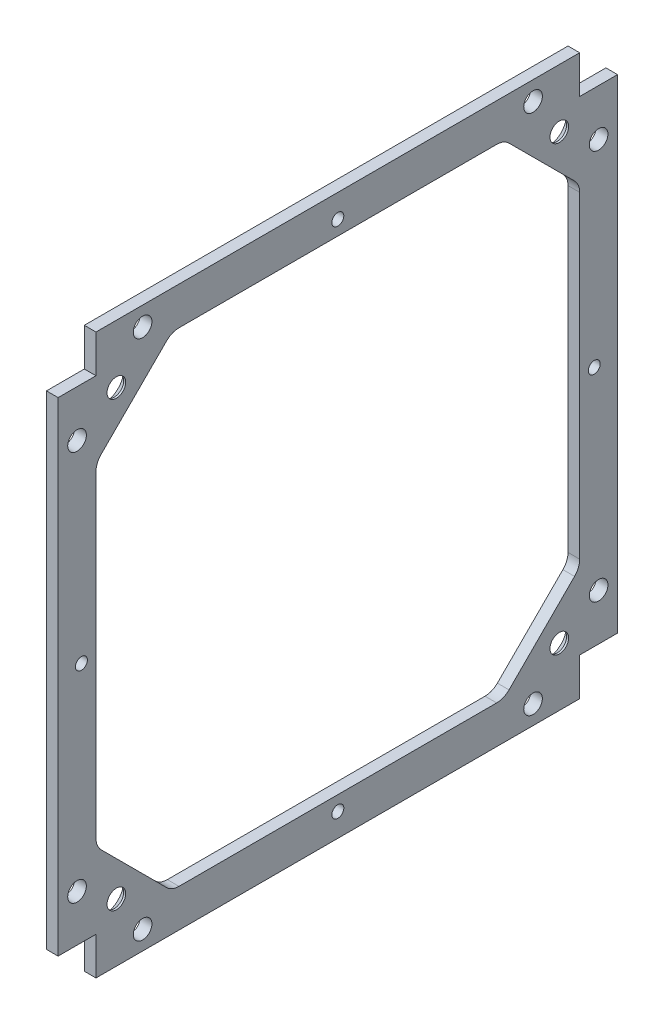
SolidWorks part; units mm, degrees
ref_plane "Front Plane" through (0, 0, 0) normal (0, 0, 1) x (1, 0, 0)
ref_plane "Top Plane" through (0, 0, 0) normal (0, 1, 0) x (1, 0, 0)
ref_plane "Right Plane" through (0, 0, 0) normal (1, 0, 0) x (0, 0, -1)
sketch "Sketch2" plane through (-51.4936, 0, 0) normal (-1, 0, 0) x (0, 0, 1)
  line L0 (0.9347, 3.4519) -> (7.4347, 3.4519)
  line L1 (7.4347, 3.4519) -> (7.4347, 86.4519)
  line L2 (0.9347, 92.9519) -> (-82.0653, 92.9519)
  line L3 (-88.5653, 86.4519) -> (-88.5653, 3.4519)
  line L4 (-82.0653, -3.0481) -> (0.9347, -3.0481)
  line L5 (0.9347, -3.0481) -> (0.9347, 3.4519)
  line L6 (-82.0653, -3.0481) -> (-82.0653, 3.4519)
  line L7 (-82.0653, 3.4519) -> (-88.5653, 3.4519)
  line L9 (-82.0653, 73.4519) -> (-82.0653, 16.4519)
  line L11 (-88.5653, 86.4519) -> (-82.0653, 86.4519)
  line L12 (-82.0653, 92.9519) -> (-82.0653, 86.4519)
  line L13 (-69.0653, 3.4519) -> (-12.0653, 3.4519)
  line L14 (-82.0653, 73.4519) -> (-69.0653, 86.4519)
  line L15 (7.4347, 86.4519) -> (0.9347, 86.4519)
  line L16 (0.9347, 92.9519) -> (0.9347, 86.4519)
  line L17 (0.9347, 16.4519) -> (0.9347, 73.4519)
  line L18 (-12.0653, 86.4519) -> (0.9347, 73.4519)
  line L19 (-12.0653, 86.4519) -> (-69.0653, 86.4519)
  line L28 (-12.0653, 3.4519) -> (0.9347, 16.4519)
  line L29 (-82.0653, 16.4519) -> (-69.0653, 3.4519)
  dimension "D21" = 13
  dimension "D1" = 6.5
  dimension "D2" = 6.5
  dimension "D3" = 6.5
  dimension "D4" = 6.5
  dimension "D5" = 6.5
  dimension "D6" = 6.5
  dimension "D7" = 13
  dimension "D8" = 6.5
  dimension "D9" = 6.5
  dimension "D10" = 13
  dimension "D11" = 6.5
  dimension "D12" = 6.5
  dimension "D14" = 13
  dimension "D15" = 13
  dimension "D16" = 13
  dimension "D17" = 13
  dimension "D18" = 13
  dimension "D19" = 83
  dimension "D20" = 83
extrude "Boss-Extrude2" add sketch "Sketch2" along normal blind 2
hole_wizard "Ø3.2 (3.2) Diameter Hole3" positions "Sketch19" profile "Sketch18" hole size "Ø3.2" standard "Ansi Metric" end condition up to next
sketch "Sketch19" plane through (-53.4936, 0, 0) normal (-1, 0, 0) x (0, 0, 1)
  line L0 (-82.0653, 3.4519) -> (-82.0653, -3.0481) construction
  line L1 (-82.0653, -3.0481) -> (0.9347, -3.0481) construction
  line L2 (0.9347, -3.0481) -> (0.9347, 3.4519) construction
  line L3 (-88.5653, 86.4519) -> (-88.5653, 3.4519) construction
  line L4 (-88.5653, 3.4519) -> (-82.0653, 3.4519) construction
  line L5 (7.4347, 3.4519) -> (7.4347, 86.4519) construction
  line L6 (0.9347, 3.4519) -> (7.4347, 3.4519) construction
  line L7 (7.4347, 86.4519) -> (0.9347, 86.4519) construction
  line L8 (0.9347, 86.4519) -> (0.9347, 92.9519) construction
  line L9 (0.9347, 92.9519) -> (-82.0653, 92.9519) construction
  line L11 (-82.0653, 92.9519) -> (-82.0653, 86.4519) construction
  line L12 (-82.0653, 86.4519) -> (-88.5653, 86.4519) construction
  point P0 (-74.0653, 0.2019)
  point P7 (-85.3153, 11.4519)
  point P9 (-85.3153, 78.4519)
  point P11 (-74.0653, 89.7019)
  point P13 (-7.0653, 89.7019)
  point P15 (4.1847, 78.4519)
  point P17 (4.1847, 11.4519)
  point P19 (-7.0653, 0.2019)
  dimension "D1" = 8
  dimension "D2" = 3.25
  dimension "D3" = 8
  dimension "D4" = 3.25
  dimension "D5" = 8
  dimension "D6" = 3.25
  dimension "D7" = 8
  dimension "D8" = 8
  dimension "D9" = 8
  dimension "D10" = 3.25
  dimension "D11" = 8
  dimension "D12" = 8
sketch "Sketch18" plane through (-53.4936, 0.2019, -74.0653) normal (0, 1, 0) x (0, 0, 1)
  line L0 (0, 0) -> (0, 2)
  line L1 (0, 2) -> (1.6, 2)
  line L2 (1.6, 2) -> (1.6, 0)
  line L5 (1.6, 0) -> (0, 0)
  line L11 (0, -6.35) -> (0, 107.95) construction
  dimension "Thru Hole Dia." = 3.2
  dimension "Thru Hole Depth" = 2
sketch "Sketch20" plane through (-53.4936, 0, 0) normal (-1, 0, 0) x (0, 0, 1)
  line L0 (-88.5653, 3.4519) -> (-82.0653, 3.4519) construction
  line L1 (-88.5653, 86.4519) -> (-88.5653, 3.4519) construction
  line L2 (-82.0653, 86.4519) -> (-88.5653, 86.4519) construction
  line L3 (-82.0653, 92.9519) -> (-82.0653, 86.4519) construction
  line L4 (0.9347, 92.9519) -> (-82.0653, 92.9519) construction
  line L5 (0.9347, 86.4519) -> (0.9347, 92.9519) construction
  line L6 (7.4347, 86.4519) -> (0.9347, 86.4519) construction
  line L7 (7.4347, 3.4519) -> (7.4347, 86.4519) construction
  point P0 (-85.5653, 6.9519)
  point P1 (-85.5653, 82.9519)
  point P2 (-78.5653, 89.9519)
  point P3 (-2.5653, 89.9519)
  point P4 (4.4347, 82.9519)
  dimension "D1" = 3.5
  dimension "D2" = 3
  dimension "D3" = 3
  dimension "D4" = 3.5
  dimension "D5" = 3.5
  dimension "D6" = 3
  dimension "D7" = 3
  dimension "D8" = 3.5
  dimension "D9" = 3.5
  dimension "D10" = 3
hole_wizard "CSK for M3 Flat Countersunk Head Screw5" positions "3DSketch2" profile "Sketch24" countersink size "M3" standard "JIS" end condition up to next
sketch3d "3DSketch2"
  line L0 (-53.4936, 3.4519, -82.0653) -> (-53.4936, -3.0481, -82.0653) construction
  line L1 (-53.4936, 3.4519, -88.5653) -> (-53.4936, 3.4519, -82.0653) construction
  line L2 (-53.4936, 92.9519, -82.0653) -> (-53.4936, 86.4519, -82.0653) construction
  line L3 (-53.4936, 86.4519, -82.0653) -> (-53.4936, 86.4519, -88.5653) construction
  line L4 (-53.4936, 86.4519, 0.9347) -> (-53.4936, 92.9519, 0.9347) construction
  line L5 (-53.4936, 86.4519, 7.4347) -> (-53.4936, 86.4519, 0.9347) construction
  line L6 (-53.4936, -3.0481, 0.9347) -> (-53.4936, 3.4519, 0.9347) construction
  line L7 (-53.4936, 3.4519, 0.9347) -> (-53.4936, 3.4519, 7.4347) construction
  point P0 (-53.4936, 6.9519, -78.5653)
  point P2 (-53.4936, 82.9519, -78.5653)
  point P4 (-53.4936, 82.9519, -2.5653)
  point P19 (-53.4936, 6.9519, -2.5653)
  dimension "D1" = 3.5
  dimension "D2" = 3.5
  dimension "D3" = 3.5
  dimension "D4" = 3.5
  dimension "D5" = 3.5
  dimension "D6" = 3.5
  dimension "D7" = 3.5
  dimension "D8" = 3.5
sketch "Sketch24" plane through (-53.4936, 6.9519, -78.5653) normal (0, 1, 0) x (0, 0, 1)
  line L0 (0, 0) -> (0, 2)
  line L1 (0, 2) -> (1.6, 2)
  line L2 (1.6, 2) -> (1.6, 1.65)
  line L3 (1.6, 1.65) -> (3.25, 0)
  line L5 (3.25, 0) -> (0, 0)
  line L6 (-1.6, 1.65) -> (-3.25, 0) construction
  line L11 (0, -6.35) -> (0, 107.95) construction
  dimension "Thru Hole Dia." = 3.2
  dimension "Thru Hole Depth" = 2
  dimension "Near C'Sink Dia." = 6.5
  dimension "Near C'Sink Angle" = 90
hole_wizard "M2.5x0.45 Tapped Hole1" positions "3DSketch3" profile "Sketch25" tap size "M2.5x0.45" standard "Ansi Metric" end condition up to next
sketch3d "3DSketch3"
  line L0 (-53.4936, 92.9519, 0.9347) -> (-53.4936, 92.9519, -82.0653) construction
  line L1 (-53.4936, 86.4519, 0.9347) -> (-53.4936, 92.9519, 0.9347) construction
  line L2 (-53.4936, 86.4519, 7.4347) -> (-53.4936, 86.4519, 0.9347) construction
  line L3 (-53.4936, 3.4519, 7.4347) -> (-53.4936, 86.4519, 7.4347) construction
  line L4 (-53.4936, -3.0481, -82.0653) -> (-53.4936, -3.0481, 0.9347) construction
  line L5 (-53.4936, -3.0481, 0.9347) -> (-53.4936, 3.4519, 0.9347) construction
  line L6 (-53.4936, 86.4519, -88.5653) -> (-53.4936, 3.4519, -88.5653) construction
  line L7 (-53.4936, 3.4519, -88.5653) -> (-53.4936, 3.4519, -82.0653) construction
  point P0 (-53.4936, 88.9519, -40.5653)
  point P2 (-53.4936, 44.9519, -84.5653)
  point P4 (-53.4936, 0.9519, -40.5653)
  point P6 (-53.4936, 44.9519, 3.4347)
  dimension "D1" = 4
  dimension "D2" = 41.5
  dimension "D3" = 41.5
  dimension "D4" = 4
  dimension "D5" = 4
  dimension "D6" = 41.5
  dimension "D7" = 4
  dimension "D8" = 41.5
sketch "Sketch25" plane through (-53.4936, 88.9519, -40.5653) normal (0, 1, 0) x (0, 0, 1)
  line L0 (0, 0) -> (0, 2)
  line L1 (0, 2) -> (1.025, 2)
  line L2 (1.025, 2) -> (1.025, 0)
  line L5 (1.025, 0) -> (0, 0)
  line L11 (0, -6.35) -> (0, 107.95) construction
  dimension "Thru Tap Drill Dia." = 2.05
  dimension "Thru Tap Drill Depth" = 2
cosmetic thread "Hole Thread1" parameters "D2"=2.5
cosmetic thread "Hole Thread2" parameters "D2"=2.5
cosmetic thread "Hole Thread3" parameters "D2"=2.5
cosmetic thread "Hole Thread4" parameters "D2"=2.5
fillet "Fillet1" radius 3 8 edges at (-52.4936, 16.4519, 0.9347) (-52.4936, 3.4519, -12.0653) (-52.4936, 3.4519, -69.0653) (-52.4936, 16.4519, -82.0653) (-52.4936, 73.4519, 0.9347) (-52.4936, 86.4519, -12.0653) (-52.4936, 73.4519, -82.0653) (-52.4936, 86.4519, -69.0653)
